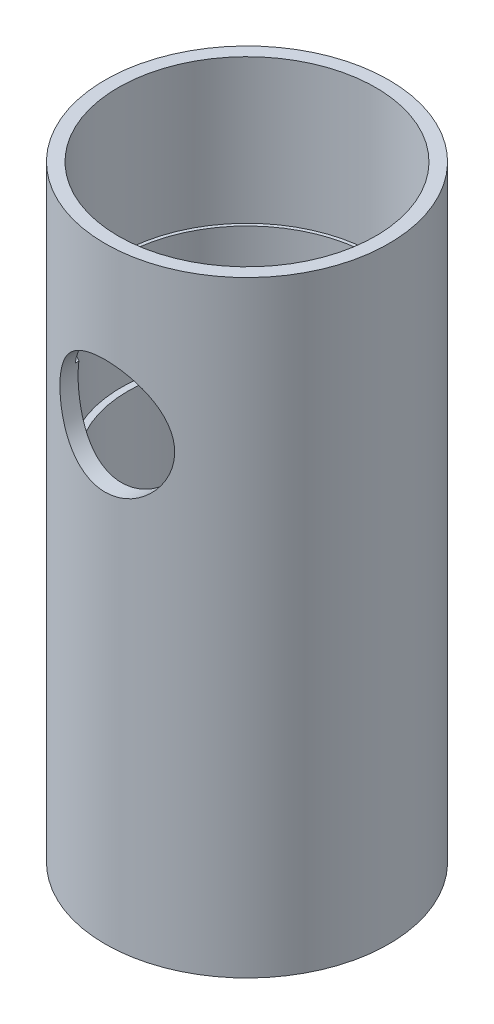
SolidWorks part; units mm, degrees
ref_plane "Front Plane" through (0, 0, 0) normal (0, 0, 1) x (1, 0, 0)
ref_plane "Top Plane" through (0, 0, 0) normal (0, 1, 0) x (1, 0, 0)
ref_plane "Right Plane" through (0, 0, 0) normal (1, 0, 0) x (0, 0, -1)
sketch "Sketch1" plane through (0, 0, 0) normal (0, 1, 0) x (1, 0, 0)
  line L0 (0, 38.25) -> (0, 43.25) construction
  circle A0 centre (0, 0) radius 38.25
  circle A1 centre (0, 0) radius 43.25
  dimension "D1" = 76.5
  dimension "D2" = 5
extrude "Boss-Extrude1" add sketch "Sketch1" along normal mid plane 185
sketch "Sketch2" plane through (0, -92.5, 0) normal (0, -1, 0) x (1, 0, 0)
  line L0 (0, 36.25) -> (0, 38.25) construction
  circle A0 centre (0, 0) radius 36.25
  circle A1 centre (0, 0) radius 38.25 construction
  circle A2 centre (0, 0) radius 38.25
  dimension "D1" = 2
extrude "Boss-Extrude2" add sketch "Sketch2" against normal blind 100 from offset 6.35 offset against normal yes
sketch "Sketch6" plane through (0, 92.5, 0) normal (0, 1, 0) x (1, 0, 0)
  line L0 (0, 38.25) -> (0, 39.25) construction
  circle A0 centre (0, 0) radius 39.25
  circle A1 centre (0, 0) radius 38.25 construction
  circle A2 centre (0, 0) radius 38.25
  dimension "D1" = 1
extrude "Cut-Extrude3" cut sketch "Sketch6" against normal blind 44
sketch "Sketch7" plane through (0, 0, 0) normal (1, 0, 0) x (0, 0, -1)
  line L0 (43.25, 92.5) -> (-43.25, 92.5) construction
  circle A0 centre (0, 44.35) radius 17.5
  dimension "D2" = 35
  dimension "D1" = 48.15
extrude "Cut-Extrude4" [suppressed] cut sketch "Sketch7" against normal through all
sketch "Sketch8" plane through (0, 0, 0) normal (0, 0, 1) x (1, 0, 0)
  line L0 (39.25, 92.5) -> (-39.25, 92.5) construction
  circle A0 centre (0, 44.35) radius 17.5
  dimension "D2" = 35
  dimension "D1" = 48.15
extrude "Cut-Extrude5" cut sketch "Sketch8" along normal through all
